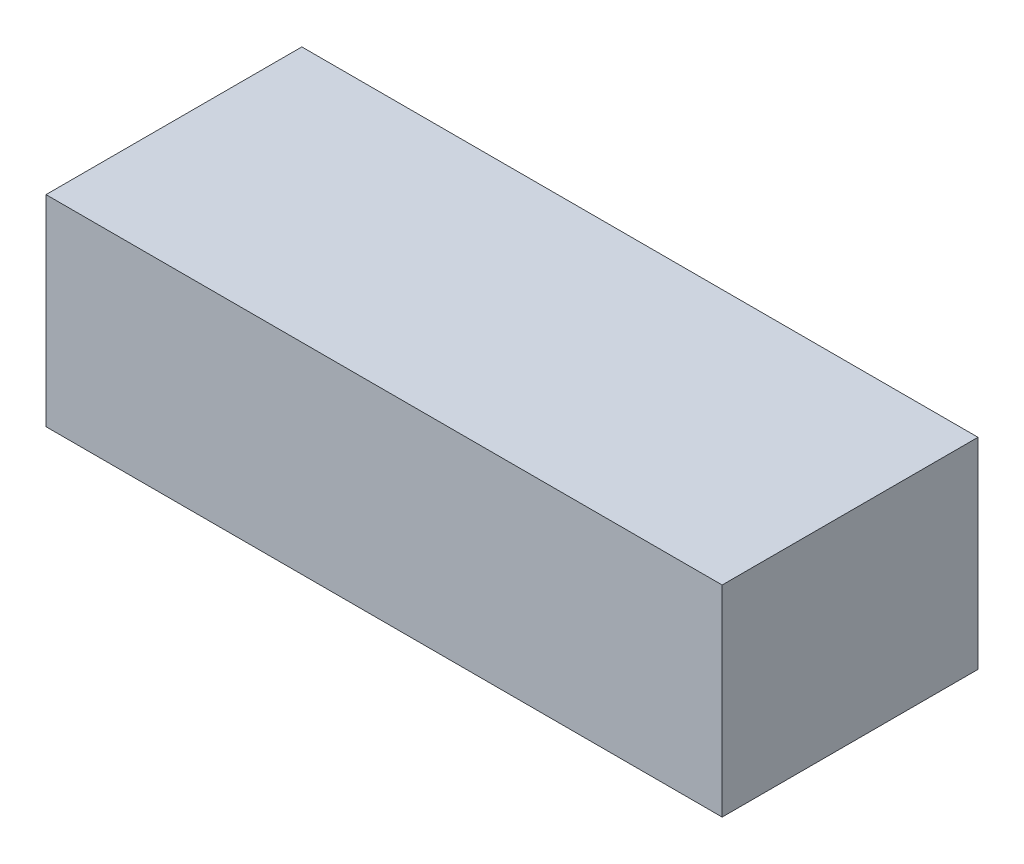
SolidWorks part; units mm, degrees
ref_plane "前视基准面" through (0, 0, 0) normal (0, 0, 1) x (1, 0, 0)
ref_plane "上视基准面" through (0, 0, 0) normal (0, 1, 0) x (1, 0, 0)
ref_plane "右视基准面" through (0, 0, 0) normal (1, 0, 0) x (0, 0, -1)
sketch "草图1" plane through (0, 0, 0) normal (0, 1, 0) x (1, 0, 0)
  line L1 (-18.7846, 7.4) -> (18.2154, 7.4)
  line L2 (-18.7846, 7.4) -> (-18.7846, -6.6)
  line L3 (-18.7846, -6.6) -> (18.2154, -6.6)
  line L4 (18.2154, 7.4) -> (18.2154, -6.6)
  dimension "D1" = 37
  dimension "D2" = 14
extrude "凸台-拉伸1" add sketch "草图1" along normal blind 11 contours L1 L4 L3 L2
